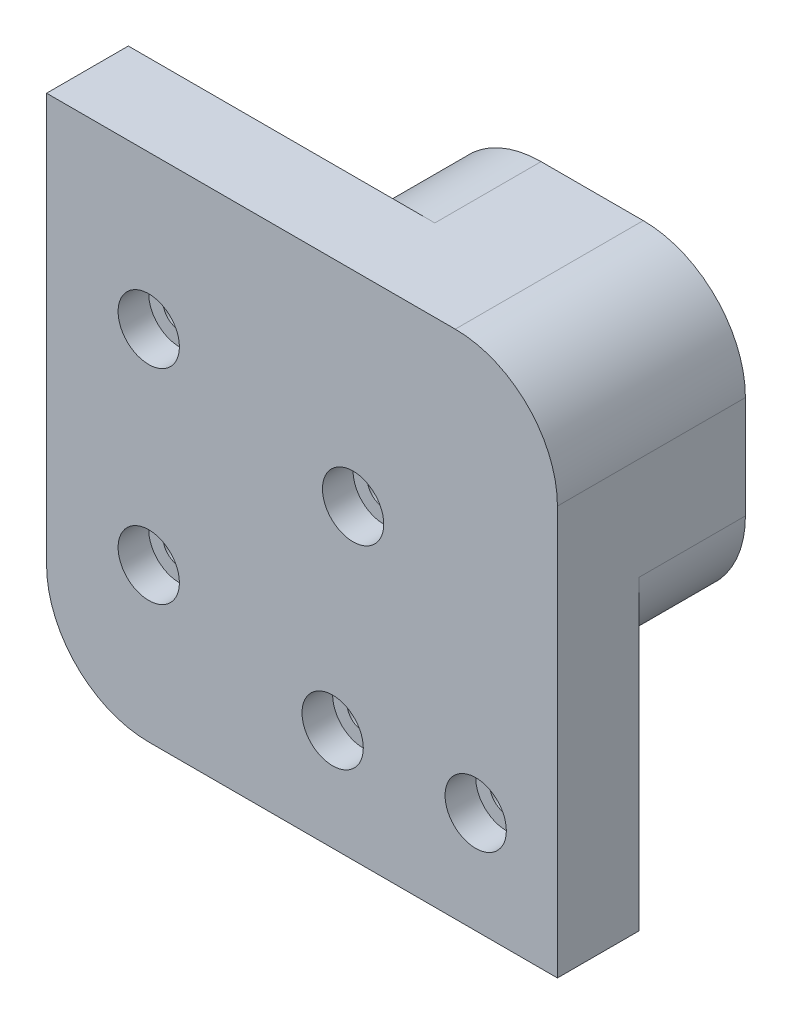
SolidWorks part; units mm, degrees
ref_plane "前视基准面" through (0, 0, 0) normal (0, 0, 1) x (1, 0, 0)
ref_plane "上视基准面" through (0, 0, 0) normal (0, 1, 0) x (1, 0, 0)
ref_plane "右视基准面" through (0, 0, 0) normal (1, 0, 0) x (0, 0, -1)
other "Configuration Table"
sketch "草图1" plane through (0, 0, 0) normal (0, 0, 1) x (1, 0, 0)
  line L0 (-10, 77.5) -> (-10, -160) construction
  line L1 (-10, -110) -> (10, -110)
  line L2 (-10, -110) -> (-10, -160)
  line L4 (10, -110) -> (10, -140.0288)
  line L5 (-10, -160) -> (40, -160)
  line L7 (10, -140.0288) -> (40, -140.0288)
  line L8 (40, -160) -> (40, -140.0288)
  line L9 (184.3942, -160) -> (10.0042, -160) construction
  line L10 (10, -130.0288) -> (10, 47.5288) construction
  line L11 (174.3942, -140.0288) -> (20, -140.0288) construction
  circle A0 centre (0, -125) radius 1.6
  circle A1 centre (0, -145) radius 1.6
  circle A2 centre (18, -150.0144) radius 1.6
  circle A3 centre (32, -150.0144) radius 1.6
  point P22 (0, -110)
  point P23 (40, -150.0144)
  dimension "D2" = 3.2
  dimension "D4" = 15
  dimension "D1" = 50
  dimension "D3" = 15
  dimension "D5" = 8
  dimension "D6" = 8
extrude "凸台-拉伸1" add sketch "草图1" along normal blind 8
sketch "草图2" plane through (0, 0, 8) normal (0, 0, 1) x (1, 0, 0)
  circle A0 centre (32, -150.0144) radius 3
  circle A1 centre (32, -150.0144) radius 1.6
  circle A2 centre (32, -150.0144) radius 1.6 construction
  circle A3 centre (18, -150.0144) radius 1.6
  circle A4 centre (18, -150.0144) radius 1.6 construction
  circle A5 centre (0, -145) radius 1.6
  circle A6 centre (0, -145) radius 1.6 construction
  circle A7 centre (0, -125) radius 1.6
  circle A8 centre (0, -125) radius 1.6 construction
  circle A9 centre (18, -150.0144) radius 3
  circle A10 centre (0, -145) radius 3
  circle A11 centre (0, -125) radius 3
  dimension "D1" = 6
  dimension "D2" = 0
  dimension "D3" = 0
  dimension "D4" = 0
  dimension "D5" = 0
extrude "切除-拉伸1" cut sketch "草图2" against normal blind 3
fillet "圆角1" radius 10 2 edges at (10, -140.0288, 4) (-10, -160, 4)
sketch "草图3" plane through (0, 0, 8) normal (0, 0, 1) x (1, 0, 0)
  line L0 (10, -130.0288) -> (10, -110) construction
  line L1 (40, -140.0288) -> (20, -140.0288) construction
  line L2 (10, -130.0288) -> (10, -110)
  line L3 (40, -140.0288) -> (20, -140.0288)
  line L4 (40, -140.0288) -> (40, -110)
  line L5 (40, -110) -> (10, -110)
  arc A0 (10, -130.0288) -> (20, -140.0288) centre (20, -130.0288) ccw construction
  arc A1 (10, -130.0288) -> (20, -140.0288) centre (20, -130.0288) ccw
  circle A2 centre (20, -130.0288) radius 2.05 construction
  arc A3 (20, -127.9788) -> (22.05, -130.0288) centre (20, -130.0288) ccw construction
  circle A4 centre (20, -130.0288) radius 2.05 construction
  arc A5 (20, -127.9788) -> (22.05, -130.0288) centre (20, -130.0288) ccw
  circle A6 centre (20, -130.0288) radius 1.6
  dimension "D1" = 3.2
extrude "凸台-拉伸2" add sketch "草图3" against normal up to surface (18.3999 mm away)
sketch "草图4" plane through (0, 0, 8) normal (0, 0, 1) x (1, 0, 0)
  circle A0 centre (20, -130.0288) radius 1.6 construction
  circle A1 centre (20, -130.0288) radius 1.6 construction
  circle A2 centre (20, -130.0288) radius 3
  dimension "D1" = 6
extrude "切除-拉伸2" cut sketch "草图4" against normal blind 3
fillet "圆角2" radius 10 3 edges at (40, -140.0288, -5.2) (10, -110, -5.2) (40, -110, -1.2)
